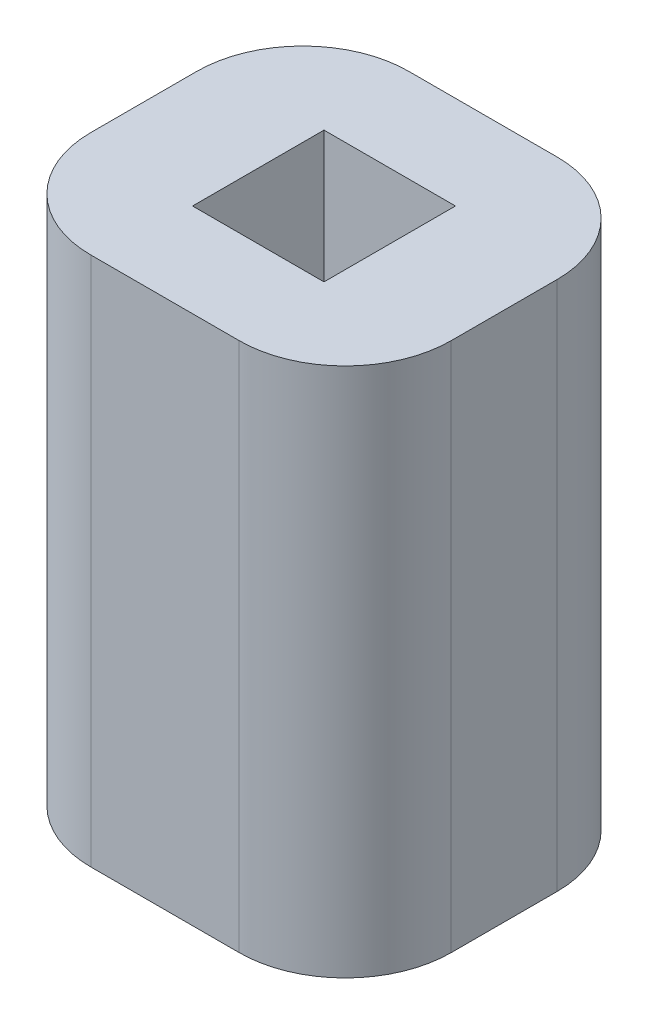
SolidWorks part; units mm, degrees
ref_plane "Front Plane" through (0, 0, 0) normal (0, 0, 1) x (1, 0, 0)
ref_plane "Top Plane" through (0, 0, 0) normal (0, 1, 0) x (1, 0, 0)
ref_plane "Right Plane" through (0, 0, 0) normal (1, 0, 0) x (0, 0, -1)
sketch "Sketch1" plane through (0, 0, 0) normal (0, 0, 1) x (1, 0, 0)
  line L1 (48.5822, 51.9145) -> (65.5822, 51.9145)
  line L2 (48.5822, 51.9145) -> (48.5822, 26.9145)
  line L3 (48.5822, 26.9145) -> (65.5822, 26.9145)
  line L4 (65.5822, 51.9145) -> (65.5822, 26.9145)
  line L5 (48.5822, 51.9145) -> (65.5822, 26.9145) construction
  line L6 (48.5822, 26.9145) -> (65.5822, 51.9145) construction
  point P0 (57.0822, 39.4145)
  dimension "D1" = 25
  dimension "D2" = 17
extrude "Boss-Extrude1" add sketch "Sketch1" along normal blind 15
sketch "Sketch2" plane through (0, 26.9145, 0) normal (0, -1, 0) x (1, 0, 0)
  line L0 (57.0822, 15) -> (57.0822, 7.5) construction
  line L1 (53.9822, 4.4) -> (60.1822, 4.4)
  line L2 (53.9822, 4.4) -> (53.9822, 10.6)
  line L3 (53.9822, 10.6) -> (60.1822, 10.6)
  line L4 (60.1822, 4.4) -> (60.1822, 10.6)
  line L5 (53.9822, 4.4) -> (60.1822, 10.6) construction
  line L6 (53.9822, 10.6) -> (60.1822, 4.4) construction
  line L7 (48.5822, 15) -> (65.5822, 15) construction
  line L8 (57.0822, 7.5) -> (65.5822, 7.5) construction
  line L9 (65.5822, 15) -> (65.5822, 0) construction
  point P0 (57.0822, 7.5)
  dimension "D1" = 6.2
  dimension "D2" = 6.2
extrude "Cut-Extrude1" cut sketch "Sketch2" against normal blind 3.25
sketch "Sketch3" plane through (0, 51.9145, 0) normal (0, 1, 0) x (1, 0, 0)
  line L4 (60.1822, -10.6) -> (60.1822, -4.4)
  line L5 (53.9822, -10.6) -> (60.1822, -10.6)
  line L6 (53.9822, -4.4) -> (53.9822, -10.6)
  line L7 (60.1822, -4.4) -> (53.9822, -4.4)
  line L8 (60.1822, -10.6) -> (60.1822, -4.4)
  line L9 (53.9822, -10.6) -> (60.1822, -10.6)
  line L10 (53.9822, -4.4) -> (53.9822, -10.6)
  line L11 (60.1822, -4.4) -> (53.9822, -4.4)
  dimension "D1" = 0
extrude "Cut-Extrude2" cut sketch "Sketch3" against normal blind 3.25
fillet "Fillet1" radius 5 4 edges at (48.5822, 39.4145, 0) (65.5822, 39.4145, 0) (48.5822, 39.4145, 15) (65.5822, 39.4145, 15)
sketch "Sketch6" plane through (0, 48.6645, 0) normal (0, 1, 0) x (1, 0, 0)
  line L0 (60.1822, -4.4) -> (53.9822, -10.6) construction
  line L2 (53.9822, -4.4) -> (60.1822, -4.4)
  line L3 (53.9822, -4.4) -> (53.9822, -10.6)
  line L4 (53.9822, -10.6) -> (60.1822, -10.6)
  line L5 (60.1822, -4.4) -> (60.1822, -10.6)
  line L6 (53.9822, -4.4) -> (60.1822, -10.6) construction
  line L7 (53.9822, -10.6) -> (60.1822, -4.4) construction
  point P4 (57.0822, -7.5)
extrude "Cut-Extrude3" cut sketch "Sketch6" against normal through all
